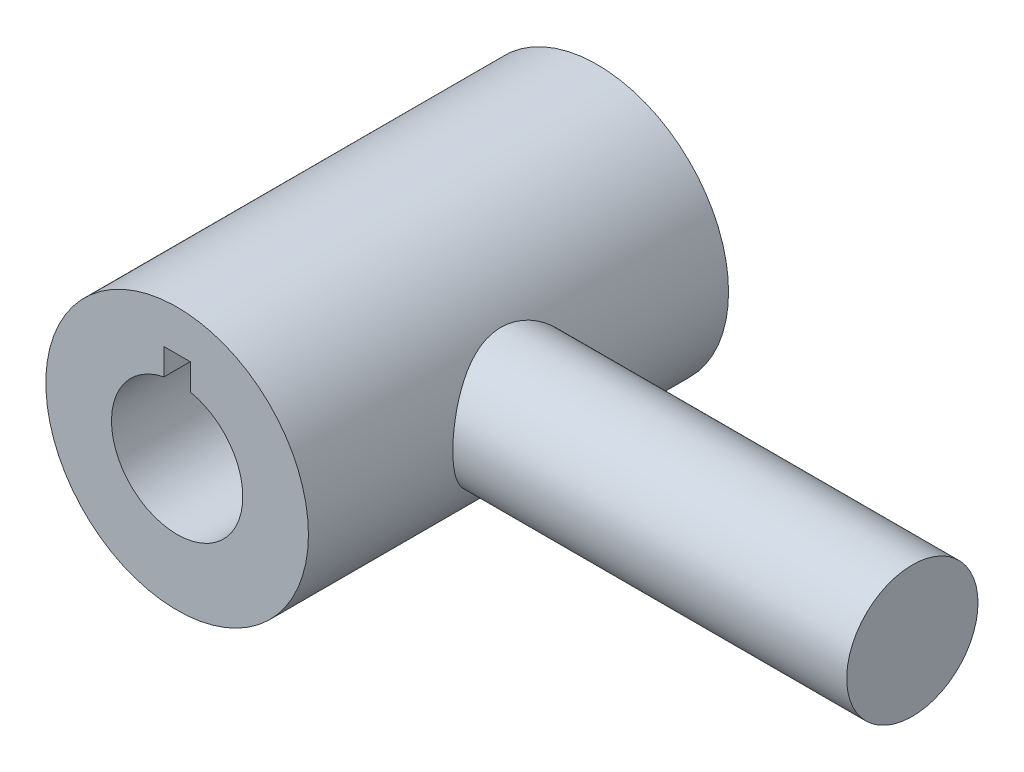
SolidWorks part; units mm, degrees
material "1060 Alloy"
ref_plane "Front Plane" through (0, 0, 0) normal (0, 0, 1) x (1, 0, 0)
ref_plane "Top Plane" through (0, 0, 0) normal (0, 1, 0) x (1, 0, 0)
ref_plane "Right Plane" through (0, 0, 0) normal (1, 0, 0) x (0, 0, -1)
sketch "Sketch1" plane through (0, 0, 0) normal (0, 0, 1) x (1, 0, 0)
  line L0 (-0.635, 3.1109) -> (-0.635, 4.3809)
  line L1 (-0.635, 4.3809) -> (0.635, 4.3809)
  line L2 (0.635, 4.3809) -> (0.635, 3.1109)
  circle A0 centre (0, 0) radius 6.35
  arc A1 (-0.635, 3.1109) -> (0.635, 3.1109) centre (0, 0) ccw
  point P7 (0, 4.3809)
  dimension "D1" = 12.7
  dimension "D2" = 6.35
  dimension "D3" = 1.27
extrude "Boss-Extrude1" add sketch "Sketch1" along normal mid plane 20.32
ref_plane "Plane1" through (25.4, 0, 0) normal (1, 0, 0) x (0, 0, -1)
sketch "Sketch2" plane through (25.4, 0, 0) normal (1, 0, 0) x (0, 0, -1)
  circle A0 centre (0, 0) radius 3.175
  dimension "D1" = 6.35
extrude "Boss-Extrude2" add sketch "Sketch2" against normal up to surface (19.05 mm away) up to face at (6.35, 0, 10.16)
